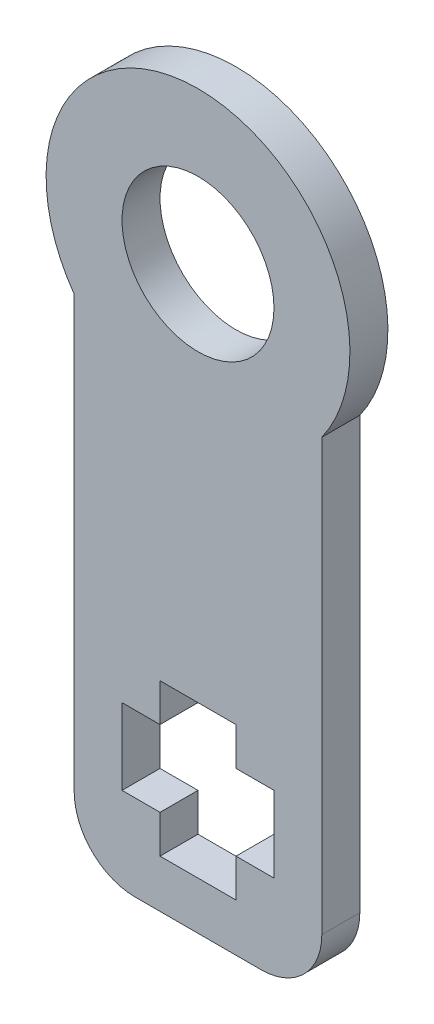
SolidWorks part; units mm, degrees
ref_plane "Front Plane" through (0, 0, 0) normal (0, 0, 1) x (1, 0, 0)
ref_plane "Top Plane" through (0, 0, 0) normal (0, 1, 0) x (1, 0, 0)
ref_plane "Right Plane" through (0, 0, 0) normal (1, 0, 0) x (0, 0, -1)
sketch "Sketch1" plane through (0, 0, 0) normal (0, 0, 1) x (1, 0, 0)
  line L0 (0, 0) -> (0, 3.175) construction
  line L1 (0, 0) -> (-3.175, 0) construction
  line L2 (-3.175, -1.5875) -> (-3.175, 1.5875)
  line L3 (-3.175, 1.5875) -> (-1.5875, 1.5875)
  line L4 (-1.5875, 1.5875) -> (-1.5875, 3.175)
  line L5 (-1.5875, 3.175) -> (1.5875, 3.175)
  line L6 (-1.5875, -3.175) -> (1.5875, -3.175)
  line L7 (-1.5875, -1.5875) -> (-1.5875, -3.175)
  line L8 (-3.175, -1.5875) -> (-1.5875, -1.5875)
  line L9 (3.175, -1.5875) -> (1.5875, -1.5875)
  line L10 (1.5875, -1.5875) -> (1.5875, -3.175)
  line L11 (1.5875, 1.5875) -> (1.5875, 3.175)
  line L12 (3.175, 1.5875) -> (1.5875, 1.5875)
  line L13 (3.175, -1.5875) -> (3.175, 1.5875)
  line L14 (0, 19.05) -> (0, 0) construction
  line L15 (-5.175, 15.3701) -> (-5.175, -5.175)
  line L16 (-5.175, -5.175) -> (5.175, -5.175)
  line L17 (5.175, -5.175) -> (5.175, 15.3701)
  line L18 (0, 0) -> (0, -5.175) construction
  arc A0 (5.175, 15.3701) -> (-5.175, 15.3701) centre (0, 19.05) ccw
  point P15 (0, -3.175)
  dimension "D1" = 12.7
  dimension "D2" = 6.35
  dimension "D3" = 1.5875
  dimension "D4" = 1.5875
  dimension "D5" = 1.5875
  dimension "D6" = 2
  dimension "D7" = 19.05
  dimension "D8" = 2
extrude "Boss-Extrude1" add sketch "Sketch1" along normal blind 1.5875
fillet "Fillet1" radius 2.54 2 edges at (5.175, -5.175, 0.7937) (-5.175, -5.175, 0.7937)
sketch "Sketch2" plane through (0, 0, 1.5875) normal (0, 0, 1) x (1, 0, 0)
  line L0 (0, 0) -> (0, 19.05) construction
  circle A0 centre (0, 19.05) radius 3.175
  dimension "D1" = 6.35
extrude "Cut-Extrude1" cut sketch "Sketch2" against normal through all
